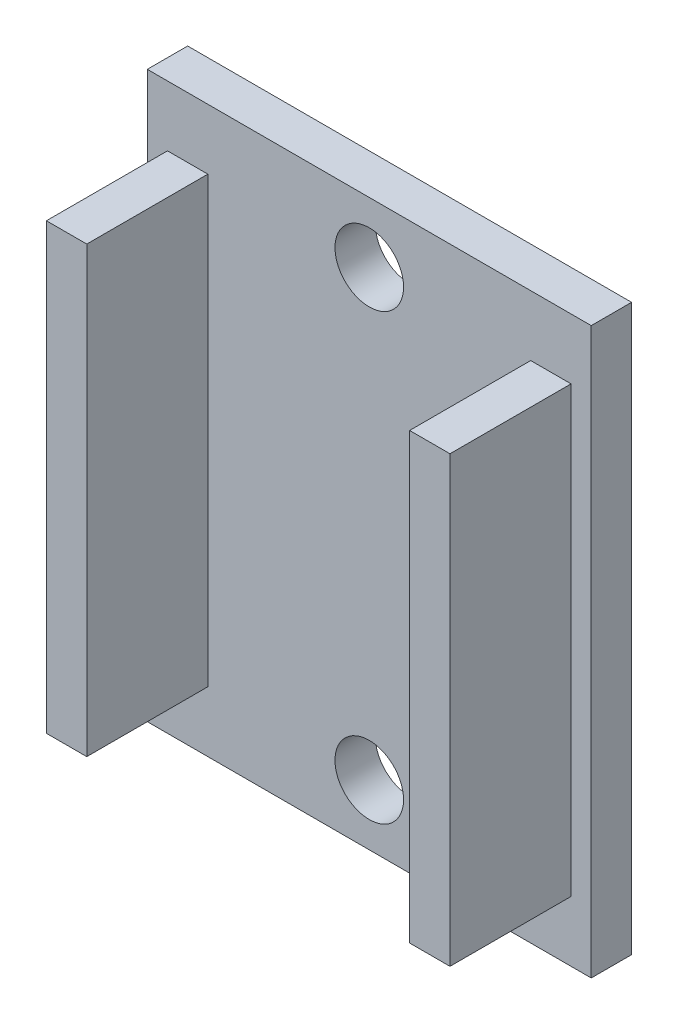
SolidWorks part; units mm, degrees
other "Battery Connector Clip"
ref_plane "Front Plane" through (0, 0, 0) normal (0, 0, 1) x (1, 0, 0)
ref_plane "Top Plane" through (0, 0, 0) normal (0, 1, 0) x (1, 0, 0)
ref_plane "Right Plane" through (0, 0, 0) normal (1, 0, 0) x (0, 0, -1)
sketch3d "Main Profile Sketch datum points"
  point P0 (0, 0, 88)
  point P1 (10, 0, 88)
  point P2 (0, 10, 88)
ref_plane "Main Profile Sketch plane" through (0, 0, 88) normal (0, 0, 1) x (1, 0, 0)
sketch "Main Profile Sketch" plane through (0, 0, 88) normal (0, 0, 1) x (1, 0, 0)
  line L0 (-214, 43) -> (-192, 43)
  line L1 (-192, 43) -> (-192, 15)
  line L2 (-214, 15) -> (-192, 15)
  line L3 (-214, 43) -> (-214, 15)
  circle A0 centre (-203, 18) radius 1.7
  circle A1 centre (-203, 40) radius 1.7
extrude "Main Extrusion" add sketch "Main Profile Sketch" along normal blind 2 separate body
sketch3d "Detail Profile 2 Sketch datum points"
  point P0 (0, 0, 90)
  point P1 (10, 0, 90)
  point P2 (0, 10, 90)
ref_plane "Detail Profile 2 Sketch plane" through (0, 0, 90) normal (0, 0, 1) x (1, 0, 0)
sketch "Detail Profile 2 Sketch" plane through (0, 0, 90) normal (0, 0, 1) x (1, 0, 0)
  line L0 (-195, 40) -> (-193, 40)
  line L1 (-193, 40) -> (-193, 18)
  line L2 (-195, 18) -> (-193, 18)
  line L3 (-195, 40) -> (-195, 18)
  line L4 (-213, 40) -> (-213, 18)
  line L5 (-213, 40) -> (-211, 40)
  line L6 (-211, 40) -> (-211, 18)
  line L7 (-213, 18) -> (-211, 18)
extrude "Detail Extrusion 2" add sketch "Detail Profile 2 Sketch" along normal blind 6
